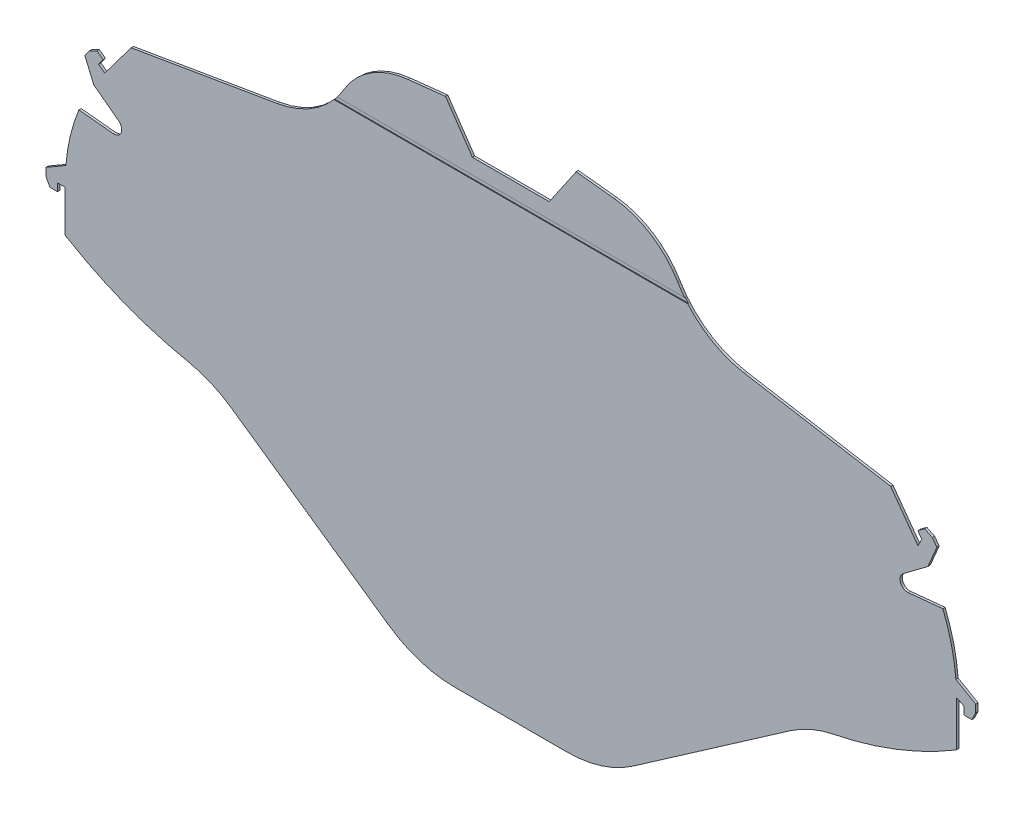
SolidWorks part; units mm, degrees
ref_plane "Front Plane" through (0, 0, 0) normal (0, 0, 1) x (1, 0, 0)
ref_plane "Top Plane" through (0, 0, 0) normal (0, 1, 0) x (1, 0, 0)
ref_plane "Right Plane" through (0, 0, 0) normal (1, 0, 0) x (0, 0, -1)
sketch "Sketch1" plane through (0, 0, 0) normal (0, 0, 1) x (1, 0, 0)
  line L0 (-24, -91.7648) -> (24, -91.7648)
  line L1 (0, 0) -> (0, -91.7648) construction
  line L2 (-10, 0) -> (-17, 10.2352)
  line L5 (-100.1804, -19.9556) -> (-60.7439, -13.2648)
  line L7 (-24, -91.7648) -> (-78.2662, -84.0567)
  line L8 (-17, 10.2352) -> (-26.9419, 9.1584)
  line L13 (-122.5, -58.7648) -> (122.5, -58.7648) construction
  line L14 (-60.7439, -13.2648) -> (-60.7439, -58.7648) construction
  line L15 (-113.5977, -28.7648) -> (-113.5977, -58.7648) construction
  line L16 (-10, 0) -> (10, 0)
  line L17 (10, 0) -> (17, 10.2352)
  line L18 (113.5977, -28.7648) -> (113.5977, -58.7648) construction
  line L19 (60.7439, -13.2648) -> (60.7439, -58.7648) construction
  line L20 (17, 10.2352) -> (26.9419, 9.1584)
  line L21 (24, -91.7648) -> (78.2662, -84.0567)
  line L22 (100.1804, -19.9556) -> (60.7439, -13.2648)
  line L23 (-17, 10.2352) -> (17, 10.2352) construction
  line L24 (0, 10.2352) -> (0, 0) construction
  arc A0 (-26.9419, 9.1584) -> (-43.4614, -1.4344) centre (-24.5729, -12.7137) ccw
  arc A1 (-43.4614, -1.4344) -> (-60.7439, -13.2648) centre (-64.9257, 11.383) cw
  arc A2 (-113.5977, -28.7648) -> (-100.1804, -19.9556) centre (-96.8349, -39.6739) cw
  arc A3 (-122.5, -58.7648) -> (-113.5977, -28.7648) centre (-67.5, -58.7648) cw
  arc A8 (-122.5, -58.7648) -> (-115.7111, -70.7648) centre (-108.5, -58.7648) ccw
  arc A9 (-115.7111, -70.7648) -> (-78.2662, -84.0567) centre (-64.2032, 14.9495) ccw
  arc A10 (115.7111, -70.7648) -> (78.2662, -84.0567) centre (64.2032, 14.9495) cw
  arc A11 (122.5, -58.7648) -> (115.7111, -70.7648) centre (108.5, -58.7648) cw
  arc A12 (122.5, -58.7648) -> (113.5977, -28.7648) centre (67.5, -58.7648) ccw
  arc A13 (113.5977, -28.7648) -> (100.1804, -19.9556) centre (96.8349, -39.6739) ccw
  arc A14 (43.4614, -1.4344) -> (60.7439, -13.2648) centre (64.9257, 11.383) ccw
  arc A15 (26.9419, 9.1584) -> (43.4614, -1.4344) centre (24.5729, -12.7137) cw
  dimension "D5" = 55
  dimension "D7" = 20
  dimension "D9" = 25
  dimension "D11" = 22
  dimension "D12" = 14
  dimension "D19" = 100
  dimension "D2" = 50.7439
  dimension "D3" = 102
  dimension "D4" = 10
  dimension "D6" = 14
  dimension "D8" = 40
  dimension "D10" = 58.7648
  dimension "D13" = 188.084
  dimension "D14" = 12.4
  dimension "D15" = 45.5
  dimension "D16" = 30
  dimension "D17" = 33
  dimension "D18" = 118.187
  dimension "D20" = 20
extrude "Main Shape" add sketch "Sketch1" along normal blind 0.6
sketch "Sketch2" plane through (0, 0, 0.6) normal (0, 0, 1) x (1, 0, 0)
  line L0 (0, 0) -> (0, -91.7648) construction
  line L1 (-24, -91.7648) -> (24, -91.7648) construction
  line L5 (-121, -59.7648) -> (-121, -57.7648)
  line L15 (-116, -59.7648) -> (-116, -70.5864)
  line L23 (113.5111, -43.4277) -> (119.6776, -41.3722) construction
  line L24 (113.5111, -43.4277) -> (106.4062, -22.1128) construction
  line L25 (109.7, -25.8648) -> (110.9, -27.4648)
  line L42 (-60.7439, -13.2648) -> (-100.1804, -19.9556) construction
  line L43 (-98.8487, -19.7297) -> (-100.1804, -19.9556)
  line L45 (-118, -59.7648) -> (-118, -61.7648)
  line L46 (-118, -61.7648) -> (-120, -61.7648)
  line L47 (-120, -61.7648) -> (-121, -59.7648)
  line L48 (-121, -57.7648) -> (-115.835, -54.7675)
  line L49 (-113.5111, -43.4277) -> (-119.6776, -41.3722) construction
  line L50 (-110.9, -27.4648) -> (-108.5664, -32.9616)
  line L57 (105.979, -29.6103) -> (106.979, -27.6103)
  line L58 (106.979, -27.6103) -> (105.9207, -26.1992)
  line L59 (105.9207, -26.1992) -> (107.7, -24.8648)
  line L60 (107.7, -24.8648) -> (109.7, -25.8648)
  line L61 (110.9, -27.4648) -> (108.5664, -32.9616)
  line L62 (121, -57.7648) -> (115.835, -54.7675)
  line L63 (120, -61.7648) -> (121, -59.7648)
  line L64 (118, -61.7648) -> (120, -61.7648)
  line L65 (118, -59.7648) -> (118, -61.7648)
  line L66 (116, -58.7648) -> (118, -59.7648)
  line L67 (98.8487, -19.7297) -> (100.1804, -19.9556)
  line L68 (105.979, -29.6103) -> (98.8487, -19.7297)
  line L69 (116, -58.7648) -> (116, -70.5864)
  line L70 (121, -59.7648) -> (121, -57.7648)
  line L71 (-118, -59.7648) -> (-116, -59.7648)
  line L72 (-118, -59.7648) -> (-121, -59.7648) construction
  line L73 (-109.7, -25.8648) -> (-110.9, -27.4648)
  line L74 (-107.7, -24.8648) -> (-109.7, -25.8648)
  line L75 (-106.1, -26.0648) -> (-107.7, -24.8648)
  line L76 (-107.3, -27.6648) -> (-106.1, -26.0648)
  line L77 (-107.3, -27.6648) -> (-105.7, -28.8648)
  line L78 (-105.7, -28.8648) -> (-98.8487, -19.7297)
  arc A9 (-106.3, -29.6648) -> (-116, -58.7648) centre (-67.5, -58.7648) ccw construction
  arc A11 (-113.5977, -28.7648) -> (-122.5, -58.7648) centre (-67.5, -58.7648) ccw construction
  arc A13 (-107.5, -28.7648) -> (-117.5, -58.7648) centre (-67.5, -58.7648) ccw construction
  arc A14 (-105.1, -30.5648) -> (-114.5, -58.7648) centre (-67.5, -58.7648) ccw construction
  arc A15 (-105.1, -30.5648) -> (-107.5, -28.7648) centre (-106.3, -29.6648) ccw construction
  arc A16 (-117.5, -58.7648) -> (-114.5, -58.7648) centre (-116, -58.7648) ccw construction
  arc A18 (106.3, -29.6648) -> (116, -58.7648) centre (67.5, -58.7648) cw construction
  arc A19 (107.5, -28.7648) -> (117.5, -58.7648) centre (67.5, -58.7648) cw construction
  arc A21 (105.1, -30.5648) -> (114.5, -58.7648) centre (67.5, -58.7648) cw construction
  arc A22 (105.1, -30.5648) -> (107.5, -28.7648) centre (106.3, -29.6648) cw construction
  arc A23 (117.5, -58.7648) -> (114.5, -58.7648) centre (116, -58.7648) cw construction
  arc A24 (122.5, -58.7648) -> (116, -70.5864) centre (108.5, -58.7648) cw
  arc A25 (113.5977, -28.7648) -> (122.5, -58.7648) centre (67.5, -58.7648) cw
  arc A26 (100.1804, -19.9556) -> (113.5977, -28.7648) centre (96.8349, -39.6739) cw
  arc A33 (-122.5, -58.7648) -> (-115.7111, -70.7648) centre (-108.5, -58.7648) ccw construction
  arc A34 (-100.1804, -19.9556) -> (-113.5977, -28.7648) centre (-96.8349, -39.6739) ccw construction
  arc A35 (-100.1804, -19.9556) -> (-113.5977, -28.7648) centre (-96.8349, -39.6739) ccw
  arc A36 (-113.5977, -28.7648) -> (-122.5, -58.7648) centre (-67.5, -58.7648) ccw
  arc A37 (-122.5, -58.7648) -> (-116, -70.5864) centre (-108.5, -58.7648) ccw
  arc A38 (115.835, -54.7675) -> (108.5664, -32.9616) centre (67.5, -58.7648) ccw
  arc A39 (-115.835, -54.7675) -> (-108.5664, -32.9616) centre (-67.5, -58.7648) cw
  point P24 (-113.5111, -43.4277)
  point P46 (113.5111, -43.4277)
  dimension "D1" = 1.5
  dimension "D2" = 5
  dimension "D3" = 2
  dimension "D7" = 1
  dimension "D4" = 2
  dimension "D5" = 2
  dimension "D6" = 2
  dimension "D8" = 5
  dimension "D9" = 3
extrude "Tabs" cut sketch "Sketch2" against normal through all both and the other way through all
sketch "Sketch5" plane through (0, 0, 0.6) normal (0, 0, 1) x (1, 0, 0)
  line L0 (-78.2662, -84.0567) -> (-24, -121.7648)
  line L1 (-24, -121.7648) -> (24, -121.7648)
  line L2 (24, -121.7648) -> (78.2662, -84.0567)
  line L3 (-78.2662, -84.0567) -> (-24, -91.7648) construction
  line L4 (24, -91.7648) -> (78.2662, -84.0567) construction
  line L5 (-24, -91.7648) -> (24, -91.7648) construction
  line L6 (24, -91.7648) -> (78.2662, -84.0567)
  line L7 (-24, -91.7648) -> (24, -91.7648)
  line L8 (-78.2662, -84.0567) -> (-24, -91.7648)
  dimension "D1" = 30
extrude "Chin guard" add sketch "Sketch5" against normal up to surface (0.6 mm away) up to face at (-0.0046, -39.2759, 0)
fillet "Fillet1" radius 30 4 edges at (-78.2662, -84.0567, 0.3) (78.2662, -84.0567, 0.3) (24, -121.7648, 0.3) (-24, -121.7648, 0.3)
sketch "Sketch7" plane through (0, 0, 0.6) normal (0, 0, 1) x (1, 0, 0)
  line L3 (-103.484, -41.411) -> (-112.4405, -40.5274)
  line L6 (-108.5664, -32.9616) -> (-102.0876, -37.8207)
  line L7 (-105.7, -28.8648) -> (-107.3, -27.6648) construction
  line L8 (0, -0.33) -> (0, 0.33) construction
  line L9 (108.5664, -32.9616) -> (102.0876, -37.8207)
  line L10 (103.484, -41.411) -> (112.4405, -40.5274)
  arc A1 (-103.484, -41.411) -> (-102.0876, -37.8207) centre (-103.2876, -39.4207) ccw
  arc A5 (-108.5664, -32.9616) -> (-115.835, -54.7675) centre (-67.5, -58.7648) ccw construction
  arc A6 (-108.5664, -32.9616) -> (-112.4405, -40.5274) centre (-67.5, -58.7648) ccw
  arc A7 (108.5664, -32.9616) -> (112.4405, -40.5274) centre (67.5, -58.7648) cw
  arc A8 (103.484, -41.411) -> (102.0876, -37.8207) centre (103.2876, -39.4207) cw
  point P0 (0, 0)
  point P20 (-113.0062, -41.9886)
  point P22 (0, 0)
  dimension "D2" = 2
  dimension "D1" = 8.5
  dimension "D3" = 9
extrude "Quick Release Notch" cut sketch "Sketch7" against normal through all both and the other way through all
sketch "Sketch8" plane through (0, 0, 0.6) normal (0, 0, 1) x (1, 0, 0)
  line L0 (10, 0) -> (-10, 0) construction
  line L1 (-50, -4) -> (50, -4)
  line L2 (-50, -4) -> (-50, -5)
  line L3 (-50, -5) -> (50, -5)
  line L4 (50, -4) -> (50, -5)
  point P5 (0, -4)
  dimension "D1" = 4
  dimension "D2" = 1
  dimension "D3" = 100
extrude "Cut-Extrude3" cut sketch "Sketch8" against normal blind 0.2
